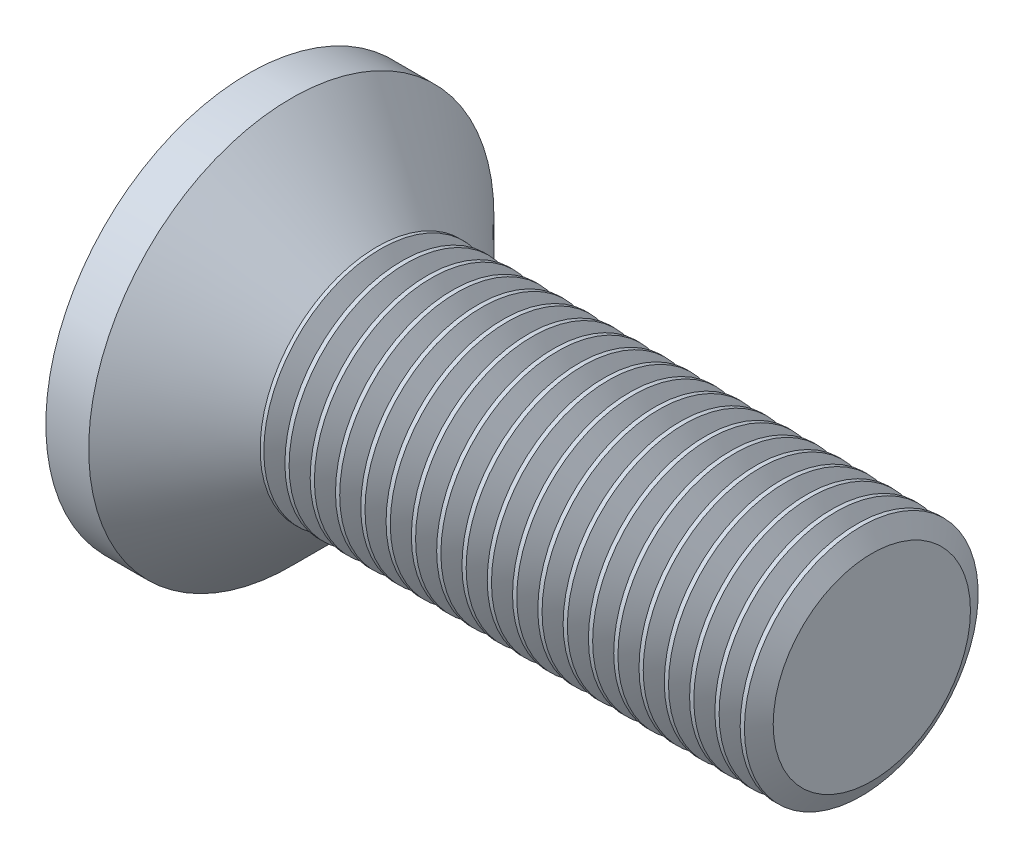
SolidWorks part; units mm, degrees
ref_plane "Front" through (0, 0, 0) normal (0, 0, 1) x (1, 0, 0)
ref_plane "Top" through (0, 0, 0) normal (0, 1, 0) x (1, 0, 0)
ref_plane "Right" through (0, 0, 0) normal (1, 0, 0) x (0, 0, -1)
other "Configuration Table"
sketch "Sketch1" plane through (0, 0, 0) normal (0, 0, 1) x (1, 0, 0)
  line L0 (8, 1.5) -> (2.65, 1.5)
  line L1 (2.65, 1.5) -> (1.65, 1.5)
  line L2 (1.65, 1.5) -> (0.55, 2.6)
  line L3 (0.55, 2.6) -> (0, 2.6)
  line L4 (8, 1.5) -> (8, 0)
  line L5 (4.5158, 0) -> (-89.8219, 0) construction
  line L6 (8, 0) -> (0, 0)
  line L7 (0, 2.6) -> (0, 0)
  dimension "d" = 3
  dimension "D1" = 45
  dimension "dk" = 5.2
  dimension "k" = 1.65
  dimension "l" = 8
  dimension "a" = 1
revolve "Base" add sketch "Sketch1" angle 360 about L5
cosmetic thread "ThreadCosmetic1" [suppressed] parameters "bb"=6.35, "THD_MINOR"=2.459
sketch "Sketch6" plane through (0, 0, 0) normal (1, 0, 0) x (0, 0, -1)
  line L0 (-1.9271, 0) -> (2.0512, 0) construction
  line L1 (0, 1.8651) -> (0, -2.0207) construction
  line L2 (0.32, 0.32) -> (0.32, 1.6)
  line L3 (0.32, 1.6) -> (-0.32, 1.6)
  line L4 (-0.32, 0.32) -> (-0.32, 1.6)
  line L5 (0.32, 0.32) -> (1.6, 0.32)
  line L6 (1.6, 0.32) -> (1.6, -0.32)
  line L7 (-1.6, 0.32) -> (-1.6, -0.32)
  line L8 (-0.32, 0.32) -> (-1.6, 0.32)
  line L9 (-0.32, -0.32) -> (-1.6, -0.32)
  line L10 (0.32, -0.32) -> (1.6, -0.32)
  line L11 (-0.32, -0.32) -> (-0.32, -1.6)
  line L12 (0.32, -1.6) -> (-0.32, -1.6)
  line L13 (0.32, -0.32) -> (0.32, -1.6)
  point P16 (-1.6, 0)
  point P17 (1.6, 0)
extrude "CrossRecess" cut sketch "Sketch6" along normal blind 0.825
draft "Draft9" type of draft neutral plane draft angle 30 faces to draft 4 face at (0.4125, 1.6, 0) face at (0.4125, 0, 1.6) face at (0.4125, -1.6, 0) face at (0.4125, 0, -1.6) neutral plane through (0, 2.6, 0) neutral plane normal (-1, 0, 0) parameters "D1"=30
fillet "Fillet5" radius 0.3 4 edges at (0.4125, -0.32, -0.32) (0.4125, 0.32, -0.32) (0.4125, 0.32, 0.32) (0.4125, -0.32, 0.32)
sketch "Sketch7" plane through (0, 0, 0) normal (1, 0, 0) x (0, 0, -1)
  line L0 (-2.0126, 0) -> (1.9757, 0) construction
  line L1 (0, 1.9314) -> (0, -2.0126) construction
  line L2 (0, 0) -> (1.5555, 1.5555) construction
  line L3 (0, 0.4782) -> (1.1314, 1.1314)
  line L4 (-1.5402, 1.5402) -> (0, 0) construction
  line L5 (0.4782, 0) -> (1.1314, 1.1314)
  line L6 (0, -0.4782) -> (1.1314, -1.1314)
  line L7 (0.4782, 0) -> (1.1314, -1.1314)
  line L8 (-0.4782, 0) -> (-1.1314, -1.1314)
  line L9 (0, -0.4782) -> (-1.1314, -1.1314)
  line L10 (-0.4782, 0) -> (-1.1314, 1.1314)
  line L11 (0, 0.4782) -> (-1.1314, 1.1314)
  dimension "D3" = 15
  dimension "m" = 3.2
extrude "Cut-Extrude3" [suppressed] cut sketch "Sketch7" along normal blind 10 draft 20
sketch "Sketch8" plane through (0, 0, 0) normal (0, 0, 1) x (1, 0, 0)
  line L0 (-17, 1.7705) -> (-18.25, 1.5)
  line L1 (-18.25, 1.5) -> (1.65, 1.5)
  line L3 (8, -1.5) -> (8, 1.5) construction
  line L6 (1.65, 1.5) -> (1.65, 6.5)
  line L7 (1.65, 6.5) -> (-17, 6.5)
  line L8 (-17, 6.5) -> (-17, 1.7705)
  line L9 (62.4753, 0.2705) -> (52.9594, 0.2705) construction
  dimension "D1" = 5
  dimension "x" = 1.25
  dimension "d" = 3
  dimension "THD_MINOR" = 2.459
  dimension "b" = 25
sketch "Sketch9" plane through (0, 0, 0) normal (0, 0, 1) x (1, 0, 0)
  line L0 (8, 1.2657) -> (8.1353, 1.5)
  line L1 (8.1353, 1.5) -> (8.1353, 1.7705)
  line L2 (8.1353, 1.7705) -> (7.8647, 1.7705)
  line L3 (7.8647, 1.7705) -> (7.8647, 1.5)
  line L4 (7.8647, 1.5) -> (8, 1.2657)
  line L5 (0, 0) -> (73.843, 0) construction
  line L6 (8, -1.5) -> (8, 1.5) construction
  dimension "D1" = 3
  dimension "D2" = 0.2705
revolve "Cut-Revolve10" cut sketch "Sketch9" angle 360 about L5
pattern_linear "LPattern10" count 20 spacing 0.3246 along (-1, 0, 0) of "Cut-Revolve10"
equation "\"D1@Sketch6\" = \"m@Sketch6\" / 5"
equation "\"D1@CrossRecess\" = \"k@Sketch1\" / 2"
equation "\"D1@Sketch9\" = \"d@Sketch1\""
equation "\"D2@Sketch9\" =  ( \"d@Sketch1\" - \"THD_MINOR@ThreadCosmetic1\" )  / 2"
equation "\"D3@LPattern10\" = \"D2@Sketch9\" * 1.2"
equation "\"D1@LPattern10\" = \"bb@ThreadCosmetic1\" / \"D3@LPattern10\" "
